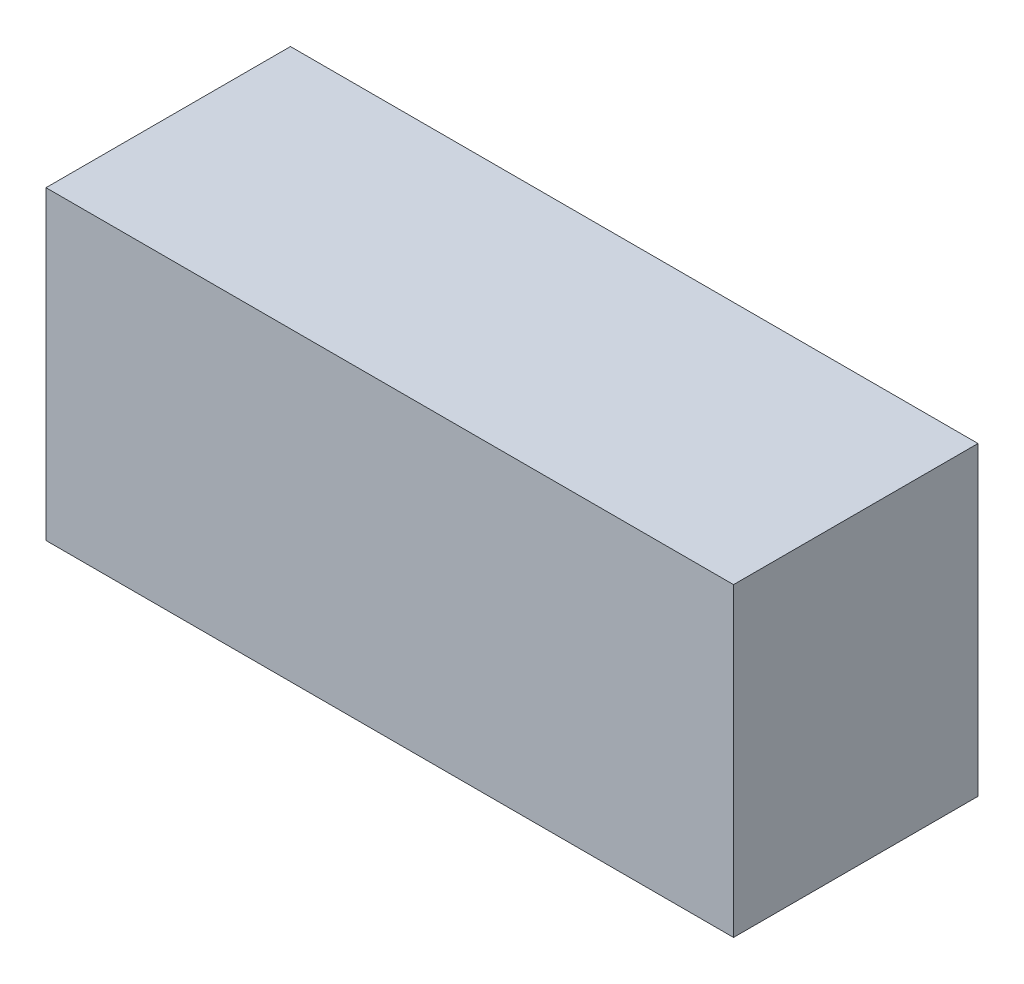
SolidWorks part; units mm, degrees
ref_plane "前视基准面" through (0, 0, 0) normal (0, 0, 1) x (1, 0, 0)
ref_plane "上视基准面" through (0, 0, 0) normal (0, 1, 0) x (1, 0, 0)
ref_plane "右视基准面" through (0, 0, 0) normal (1, 0, 0) x (0, 0, -1)
sketch "草图1" plane through (0, 0, 0) normal (0, 1, 0) x (1, 0, 0)
  line L1 (-22.5, 8) -> (22.5, 8)
  line L2 (-22.5, 8) -> (-22.5, -8)
  line L3 (-22.5, -8) -> (22.5, -8)
  line L4 (22.5, 8) -> (22.5, -8)
  line L5 (0, -8) -> (0, 8) construction
  line L6 (-22.5, 0) -> (22.5, 0) construction
  point P0 (0, 0)
  dimension "D1" = 45
  dimension "D2" = 16
extrude "凸台-拉伸1" add sketch "草图1" along normal blind 20
